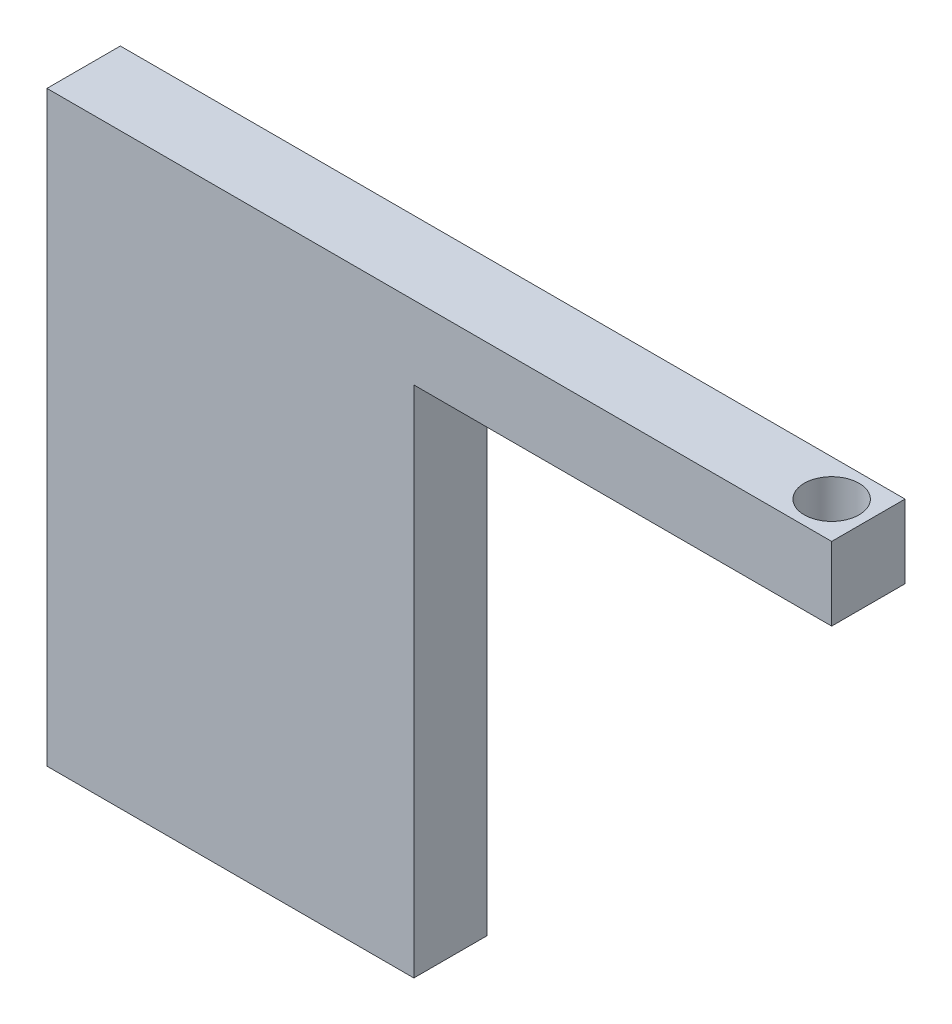
SolidWorks part; units mm, degrees
ref_plane "Front Plane" through (0, 0, 0) normal (0, 0, 1) x (1, 0, 0)
ref_plane "Top Plane" through (0, 0, 0) normal (0, 1, 0) x (1, 0, 0)
ref_plane "Right Plane" through (0, 0, 0) normal (1, 0, 0) x (0, 0, -1)
sketch "Sketch1" plane through (0, 0, 0) normal (0, 0, 1) x (1, 0, 0)
  line L0 (0.3306, 197.9339) -> (0.3306, 187.9339)
  line L1 (0.3306, 187.9339) -> (-56.6116, 187.9339)
  line L2 (-56.6116, 187.9339) -> (-56.6116, 117.9339)
  line L3 (-56.6116, 117.9339) -> (-106.6116, 117.9339)
  line L4 (-106.6116, 117.9339) -> (-106.6116, 197.9339)
  line L5 (-106.6116, 197.9339) -> (0.3306, 197.9339)
  dimension "D1" = 50
  dimension "D2" = 80
  dimension "D3" = 10
  dimension "D4" = 106.9421
extrude "Boss-Extrude1" add sketch "Sketch1" along normal blind 10
sketch "Sketch2" plane through (0, 197.9339, 0) normal (0, 1, 0) x (1, 0, 0)
  line L0 (0.3306, -10) -> (0.3306, 0) construction
  line L1 (0.3306, 0) -> (-106.6116, 0) construction
  circle A0 centre (-4.6694, -5) radius 3.7353
  dimension "D1" = 5
  dimension "D2" = 5
extrude "Cut-Extrude1" cut sketch "Sketch2" against normal through all both and the other way through all
